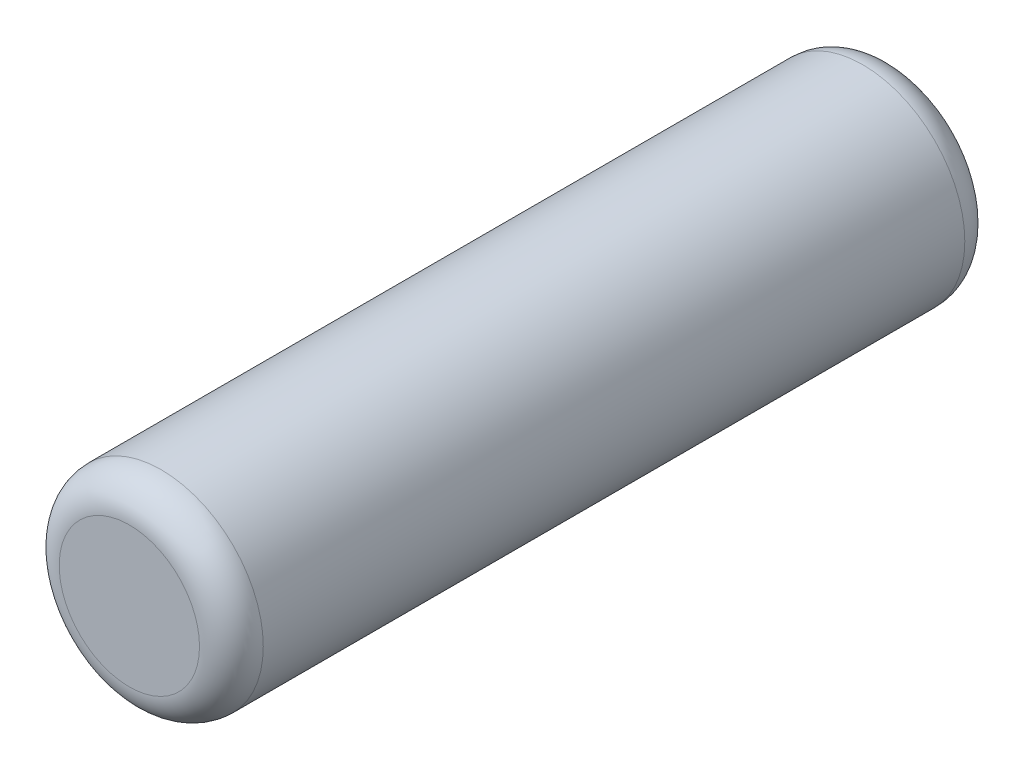
SolidWorks part; units mm, degrees
ref_plane "정면" through (0, 0, 0) normal (0, 0, 1) x (1, 0, 0)
ref_plane "윗면" through (0, 0, 0) normal (0, 1, 0) x (1, 0, 0)
ref_plane "우측면" through (0, 0, 0) normal (1, 0, 0) x (0, 0, -1)
sketch "스케치1" plane through (0, 0, 0) normal (0, 0, 1) x (1, 0, 0)
  circle A0 centre (0, 0) radius 3.2
  dimension "D1" = 6.4
extrude "보스-돌출1" add sketch "스케치1" along normal blind 24
fillet "필렛1" radius 1 2 edges at (3.2, 0, 0) (3.2, 0, 24)
